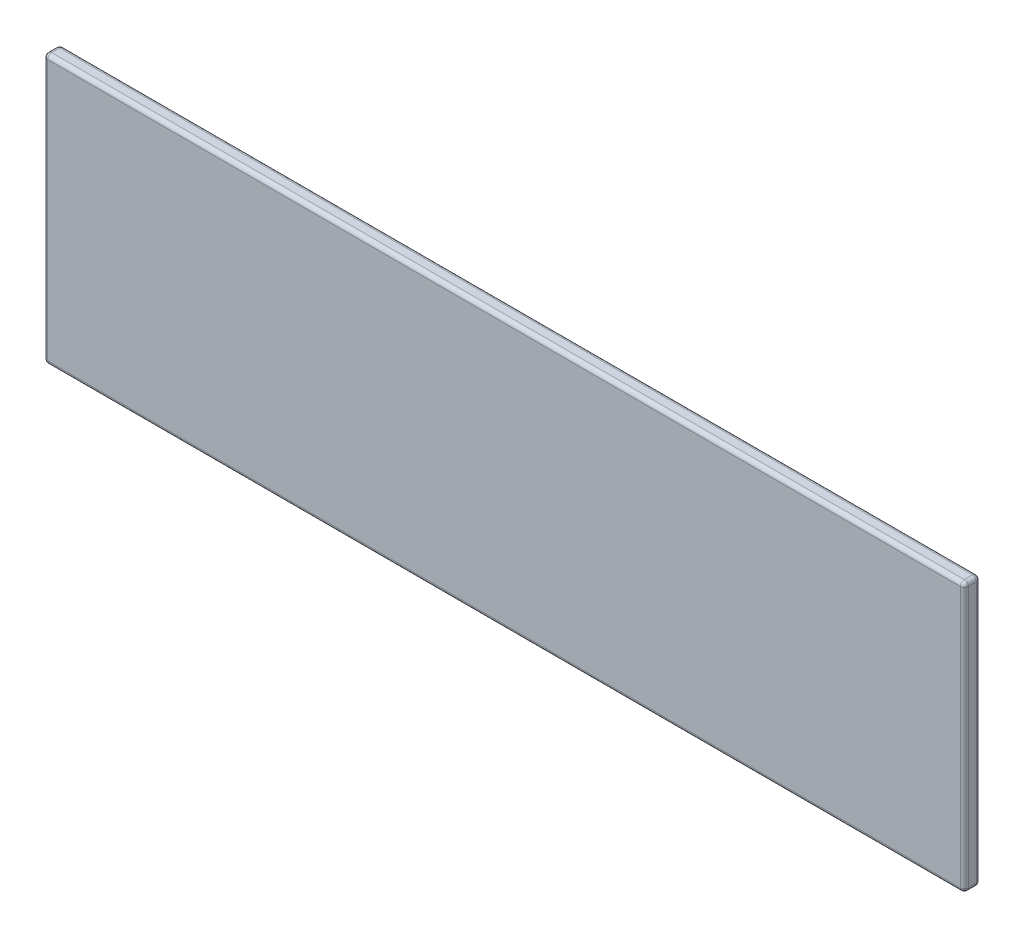
SolidWorks part; units mm, degrees
ref_plane "Front Plane" through (0, 0, 0) normal (0, 0, 1) x (1, 0, 0)
ref_plane "Top Plane" through (0, 0, 0) normal (0, 1, 0) x (1, 0, 0)
ref_plane "Right Plane" through (0, 0, 0) normal (1, 0, 0) x (0, 0, -1)
sketch "Sketch1" plane through (0, 0, 0) normal (0, 0, 1) x (1, 0, 0)
  line L1 (-57.35, -16.75) -> (57.35, -16.75)
  line L2 (-57.35, -16.75) -> (-57.35, 16.75)
  line L3 (-57.35, 16.75) -> (57.35, 16.75)
  line L4 (57.35, -16.75) -> (57.35, 16.75)
  line L5 (-57.35, -16.75) -> (57.35, 16.75) construction
  line L6 (-57.35, 16.75) -> (57.35, -16.75) construction
  point P0 (0, 0)
  dimension "D1" = 114.7
  dimension "D2" = 33.5
extrude "Boss-Extrude1" add sketch "Sketch1" along normal blind 2
fillet "Fillet1" radius 0.5 12 edges at (0, -16.75, 2) (0, -16.75, 0) (-57.35, 0, 2) (-57.35, -16.75, 1) (-57.35, 0, 0) (0, 16.75, 2) (-57.35, 16.75, 1) (0, 16.75, 0) (57.35, -16.75, 1) (57.35, 0, 2) (57.35, 16.75, 1) (57.35, 0, 0)
